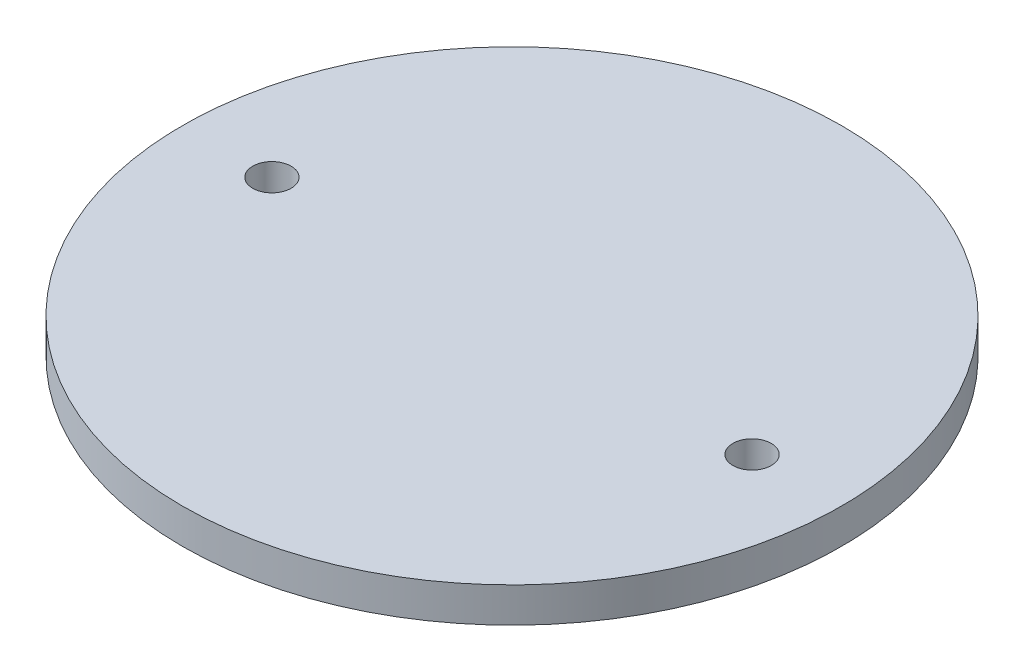
SolidWorks part; units mm, degrees
material "Balsa"
ref_plane "Front Plane" through (0, 0, 0) normal (0, 0, 1) x (1, 0, 0)
ref_plane "Top Plane" through (0, 0, 0) normal (0, 1, 0) x (1, 0, 0)
ref_plane "Right Plane" through (0, 0, 0) normal (1, 0, 0) x (0, 0, -1)
sketch "Sketch1" plane through (0, 0, 0) normal (0, 1, 0) x (1, 0, 0)
  line L0 (-37.75, 0) -> (37.75, 0) construction
  line L1 (0, 37.75) -> (0, -37.75) construction
  circle A0 centre (0, 0) radius 37.75
  circle A1 centre (-27.5, 0) radius 2.2
  circle A2 centre (27.5, 0) radius 2.2
  dimension "D1" = 55
  dimension "D2" = 75.5
  dimension "D3" = 4.4
extrude "Boss-Extrude1" add sketch "Sketch1" along normal blind 4
